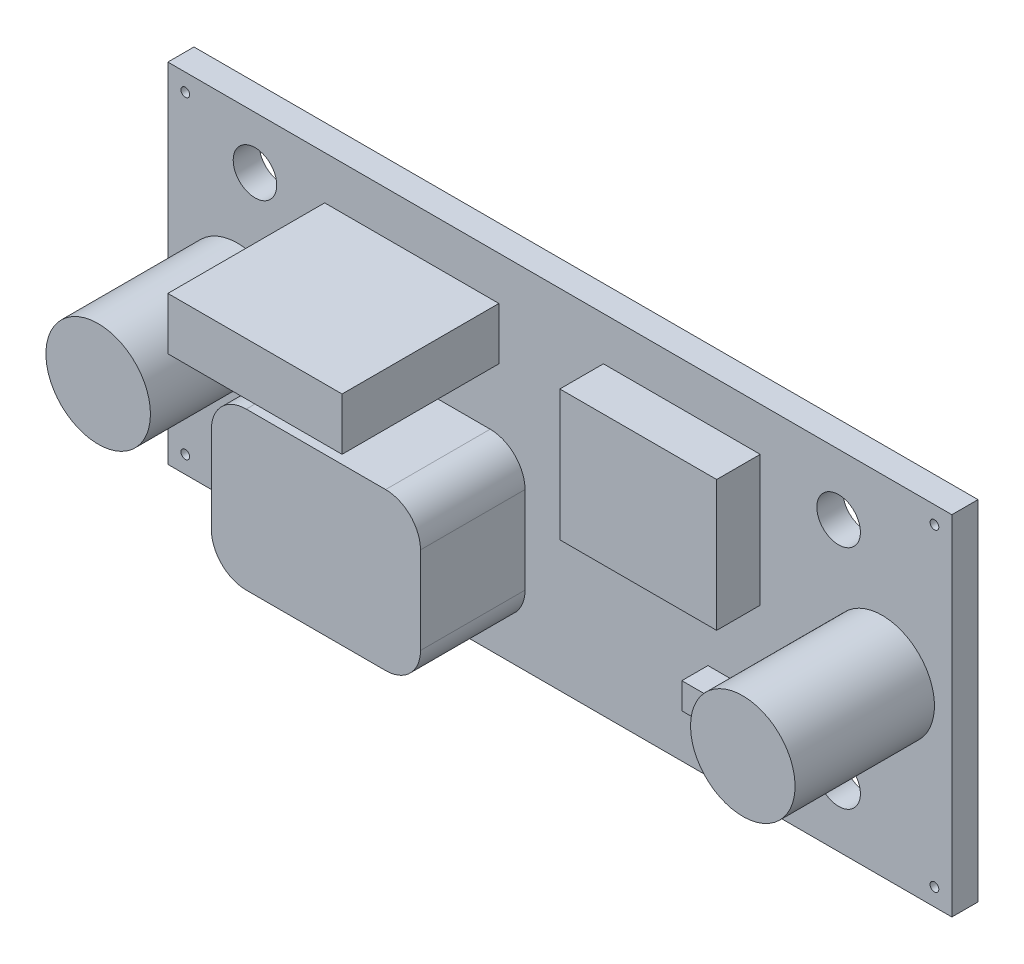
SolidWorks part; units mm, degrees
ref_plane "Front Plane" through (0, 0, 0) normal (0, 0, 1) x (1, 0, 0)
ref_plane "Top Plane" through (0, 0, 0) normal (0, 1, 0) x (1, 0, 0)
ref_plane "Right Plane" through (0, 0, 0) normal (1, 0, 0) x (0, 0, -1)
sketch "Sketch1" plane through (0, 0, 0) normal (0, 0, 1) x (1, 0, 0)
  line L1 (-22.5, 10) -> (22.5, 10)
  line L2 (-22.5, 10) -> (-22.5, -10)
  line L3 (-22.5, -10) -> (22.5, -10)
  line L4 (22.5, 10) -> (22.5, -10)
  line L5 (-22.5, 10) -> (22.5, -10) construction
  line L6 (-22.5, -10) -> (22.5, 10) construction
  point P0 (0, 0)
  dimension "D1" = 45
  dimension "D2" = 20
extrude "Boss-Extrude1" add sketch "Sketch1" along normal blind 1.5
sketch "Sketch2" plane through (0, 0, 1.5) normal (0, 0, 1) x (1, 0, 0)
  line L0 (-22.5, 10) -> (-22.5, -10) construction
  line L1 (-22.5, -10) -> (22.5, -10) construction
  line L2 (0, 9.2301) -> (0, -9.3624) construction
  circle A0 centre (-18.5, 0) radius 3
  circle A1 centre (18.5, 0) radius 3
  dimension "D2" = 6
  dimension "D1" = 4
  dimension "D3" = 10
extrude "Boss-Extrude3" add sketch "Sketch2" along normal blind 8
sketch "Sketch3" plane through (0, 0, 1.5) normal (0, 0, 1) x (1, 0, 0)
  line L0 (0, 9.0316) -> (0, -8.6346) construction
  line L1 (22.5, 10) -> (-22.5, 10) construction
  line L2 (-13.5, 7.5) -> (-3.5, 7.5)
  line L3 (-13.5, 7.5) -> (-13.5, 4.5)
  line L4 (-13.5, 4.5) -> (-3.5, 4.5)
  line L5 (-3.5, 7.5) -> (-3.5, 4.5)
  line L6 (-13.5, 7.5) -> (-3.5, 4.5) construction
  line L7 (-13.5, 4.5) -> (-3.5, 7.5) construction
  line L8 (-22.5, 10) -> (-22.5, -10) construction
  point P2 (-8.5, 6)
  dimension "D1" = 10
  dimension "D2" = 3
  dimension "D3" = 2.5
  dimension "D4" = 9
extrude "Boss-Extrude4" add sketch "Sketch3" along normal blind 9
sketch "Sketch5" plane through (0, 0, 1.5) normal (0, 0, 1) x (1, 0, 0)
  line L0 (-22.5, -10) -> (22.5, -10) construction
  line L1 (-12, 1) -> (-4, 1)
  line L2 (-14, -1) -> (-14, -6)
  line L3 (-12, -8) -> (-4, -8)
  line L4 (-2, -1) -> (-2, -6)
  line L5 (-14, 1) -> (-2, -8) construction
  line L6 (-14, -8) -> (-2, 1) construction
  line L7 (-22.5, 10) -> (-22.5, -10) construction
  arc A0 (-14, -6) -> (-12, -8) centre (-12, -6) ccw
  arc A1 (-4, -8) -> (-2, -6) centre (-4, -6) ccw
  arc A2 (-2, -1) -> (-4, 1) centre (-4, -1) ccw
  arc A3 (-12, 1) -> (-14, -1) centre (-12, -1) ccw
  point P0 (-8, -3.5)
  dimension "D5" = 2
  dimension "D1" = 12
  dimension "D2" = 9
  dimension "D3" = 2
  dimension "D4" = 8.5
extrude "Boss-Extrude5" add sketch "Sketch5" along normal blind 6
sketch "Sketch6" plane through (0, 0, 1.5) normal (0, 0, 1) x (1, 0, 0)
  line L0 (22.5, 10) -> (-22.5, 10) construction
  line L1 (2.5, 7.5) -> (11.5, 7.5)
  line L2 (2.5, 7.5) -> (2.5, 0)
  line L3 (2.5, 0) -> (11.5, 0)
  line L4 (11.5, 7.5) -> (11.5, 0)
  line L5 (2.5, 7.5) -> (11.5, 0) construction
  line L6 (2.5, 0) -> (11.5, 7.5) construction
  line L7 (22.5, -10) -> (22.5, 10) construction
  point P0 (7, 3.75)
  dimension "D1" = 7.5
  dimension "D2" = 2.5
  dimension "D3" = 9
  dimension "D4" = 11
extrude "Boss-Extrude6" add sketch "Sketch6" along normal blind 2.5
sketch "Sketch7" plane through (0, 0, 1.5) normal (0, 0, 1) x (1, 0, 0)
  line L0 (-22.5, -10) -> (22.5, -10) construction
  line L7 (8.5, -4.5) -> (11.5, -4.5)
  line L8 (8.5, -4.5) -> (8.5, -6)
  line L9 (8.5, -6) -> (11.5, -6)
  line L10 (11.5, -4.5) -> (11.5, -6)
  line L11 (8.5, -4.5) -> (11.5, -6) construction
  line L12 (8.5, -6) -> (11.5, -4.5) construction
  line L13 (22.5, -10) -> (22.5, 10) construction
  point P5 (10, -5.25)
  dimension "D1" = 3
  dimension "D2" = 1.5
  dimension "D5" = 4
  dimension "D6" = 11
extrude "Boss-Extrude7" add sketch "Sketch7" along normal blind 1.5
sketch "Sketch9" plane through (0, 0, 1.5) normal (0, 0, 1) x (1, 0, 0)
  line L0 (-22.5, -10) -> (22.5, -10) construction
  line L1 (-22.5, 10) -> (-22.5, -10) construction
  line L2 (-22.5, 0) -> (23.3812, 0) construction
  circle A0 centre (-17.5, -7) radius 1.25
  circle A1 centre (-17.5, 7) radius 1.25
  dimension "D1" = 2.5
  dimension "D2" = 3
  dimension "D3" = 5
extrude "Cut-Extrude1" cut sketch "Sketch9" against normal through all
sketch "Sketch10" plane through (0, 0, 1.5) normal (0, 0, 1) x (1, 0, 0)
  line L0 (22.5, -10) -> (22.5, 10) construction
  line L1 (-22.5, -10) -> (22.5, -10) construction
  line L2 (22.9406, 0) -> (-23.455, 0) construction
  circle A0 centre (16, 6.5) radius 1.25
  circle A1 centre (16, -6.5) radius 1.25
  dimension "D1" = 2.5
  dimension "D2" = 6.5
  dimension "D3" = 16.5
extrude "Cut-Extrude2" cut sketch "Sketch10" against normal through all
sketch "Sketch12" plane through (0, 0, 1.5) normal (0, 0, 1) x (1, 0, 0)
  line L0 (-22.5, 10) -> (-22.5, -10) construction
  line L1 (22.5, 10) -> (-22.5, 10) construction
  line L2 (22.5, -10) -> (22.5, 10) construction
  line L3 (-22.5, -10) -> (22.5, -10) construction
  circle A0 centre (-21.5, 9) radius 0.25
  circle A1 centre (21.5, 9) radius 0.25
  circle A2 centre (21.5, -9) radius 0.25
  circle A3 centre (-21.5, -9) radius 0.25
  dimension "D1" = 0.5
  dimension "D2" = 0.5
  dimension "D3" = 0.5
  dimension "D4" = 0.5
  dimension "D5" = 1
  dimension "D6" = 1
  dimension "D7" = 1
  dimension "D8" = 1
  dimension "D9" = 1
  dimension "D10" = 1
  dimension "D11" = 1
  dimension "D12" = 1
extrude "Cut-Extrude3" cut sketch "Sketch12" against normal blind 1.5
